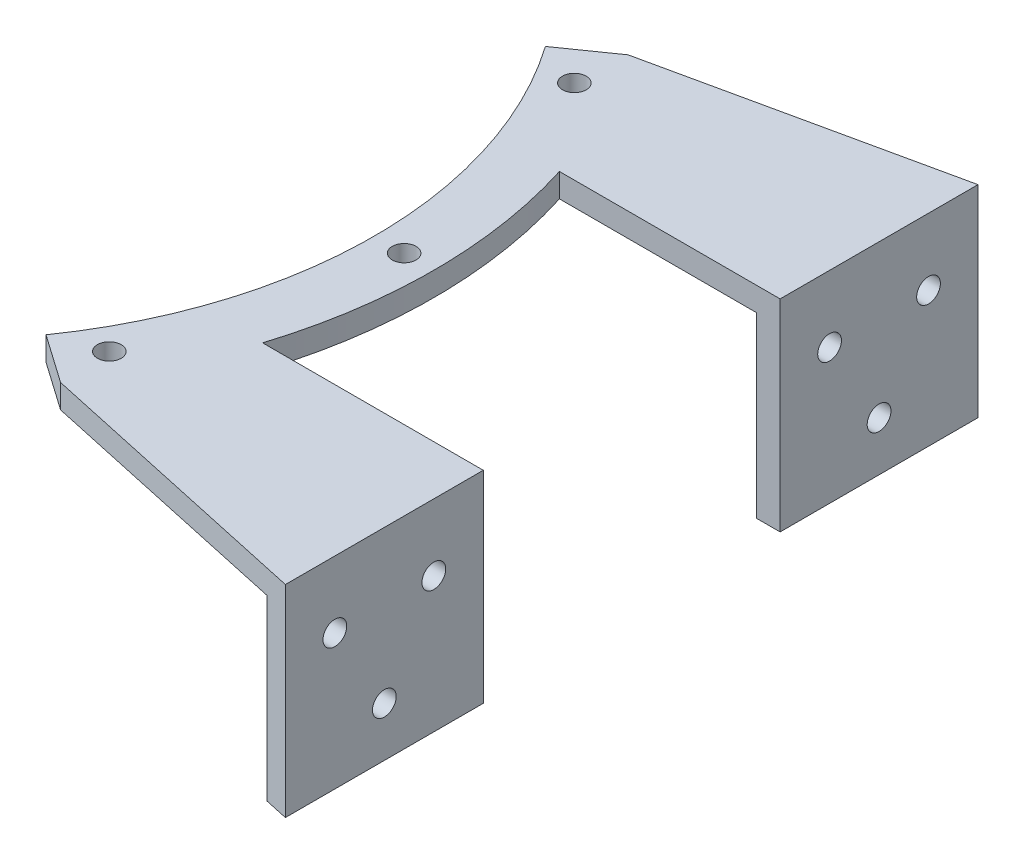
SolidWorks part; units mm, degrees
ref_plane "Front Plane" through (0, 0, 0) normal (0, 0, 1) x (1, 0, 0)
ref_plane "Top Plane" through (0, 0, 0) normal (0, 1, 0) x (1, 0, 0)
ref_plane "Right Plane" through (0, 0, 0) normal (1, 0, 0) x (0, 0, -1)
sketch "Sketch1" plane through (0, 0, 0) normal (0, 1, 0) x (1, 0, 0)
  line L0 (0, 0) -> (250, 0) construction
  line L1 (0, 0) -> (216.5064, 125) construction
  line L2 (0, 0) -> (216.5064, -125) construction
  line L3 (216.5064, 125) -> (216.5064, -125) construction
  line L5 (204.788, 143.3941) -> (204.788, -143.3941) construction
  line L11 (350, 175) -> (350, 75)
  line L12 (350, 75) -> (238.4848, 75)
  line L13 (350, -175) -> (350, -75)
  line L14 (350, -75) -> (238.4848, -75)
  line L15 (0, 0) -> (204.788, 143.3941) construction
  line L16 (0, 0) -> (204.788, -143.3941) construction
  line L17 (180.2134, 126.1868) -> (204.788, 143.3941)
  line L18 (180.2134, -126.1868) -> (204.788, -143.3941)
  line L21 (204.788, 143.3941) -> (350, 175)
  line L22 (204.788, -143.3941) -> (350, -175)
  arc A0 (180.2134, -126.1868) -> (180.2134, 126.1868) centre (0, 0) ccw
  arc A1 (204.788, -143.3941) -> (204.788, 143.3941) centre (0, 0) ccw construction
  circle A2 centre (0, 0) radius 235 construction
  circle A3 centre (203.516, -117.5) radius 6
  circle A4 centre (235, 0) radius 6
  circle A5 centre (203.516, 117.5) radius 6
  arc A8 (238.4848, -75) -> (238.4848, 75) centre (0, 0) ccw
  dimension "D11" = 250
  dimension "D2" = 220
  dimension "D4" = 470
  dimension "D5" = 12
  dimension "D3" = 60
  dimension "D6" = 100
  dimension "D7" = 100
  dimension "D8" = 350
  dimension "D9" = 70
  dimension "D10" = 350
extrude "Boss-Extrude2" add sketch "Sketch1" along normal blind 12
sketch "Sketch2" plane through (0, 0, 0) normal (0, -1, 0) x (-1, 0, 0)
  line L0 (-350, -175) -> (-350, -75)
  line L1 (-350, -75) -> (-338, -75)
  line L2 (-350, -75) -> (-238.4848, -75) construction
  line L3 (-338, -75) -> (-338, -172.3882)
  line L4 (-204.788, -143.3941) -> (-350, -175) construction
  line L5 (-338, -172.3882) -> (-350, -175)
  line L6 (-350, 75) -> (-350, 175)
  line L7 (-350, 175) -> (-338, 172.3882)
  line L8 (-350, 175) -> (-204.788, 143.3941) construction
  line L9 (-338, 172.3882) -> (-338, 75)
  line L10 (-238.4848, 75) -> (-350, 75) construction
  line L11 (-338, 75) -> (-350, 75)
  dimension "D1" = 12
extrude "Boss-Extrude3" add sketch "Sketch2" along normal blind 90
sketch "Sketch4" plane through (338, 0, 0) normal (-1, 0, 0) x (0, 0, 1)
  line L0 (-55.6551, -65) -> (-154.4826, -65) construction
  line L3 (0, 0) -> (0, -141.9458) construction
  circle A0 centre (-150, -21.6987) radius 6
  circle A6 centre (-125, -65) radius 6
  circle A7 centre (-100, -21.6987) radius 6
  circle A8 centre (125, -65) radius 6
  circle A9 centre (150, -21.6987) radius 6
  circle A10 centre (100, -21.6987) radius 6
  dimension "D5" = 12
  dimension "D1" = 65
  dimension "D2" = 50
  dimension "D3" = 50
  dimension "D4" = 50
  dimension "D6" = 150
extrude "Cut-Extrude1" cut sketch "Sketch4" against normal through all
equation "\"mbtOD\" = 600"
equation "\"mbtT\" = 6"
equation "\"mbtL\" = 3000"
equation "\"mbtFlangeOD\" = 700"
equation "\"mbtFlangeT\" = 12"
equation "\"mbtFlangeBoltCircleDia\" = 650"
equation "\"mbtFlangeHoleDia\" = 12"
equation "\"mbtOringSize\" = 10 "
equation "\"mbtOringDia\" = 620"
equation "\"mbtWidth\" = 2250"
equation "\"skiWidth\" = 1250"
equation "\"mbtCapL\" = 500"
equation "\"vbtRearOD\" = 500"
equation "\"vbtRearT\" = 6.25"
equation "\"vbtRearFlangeOD\" = 600"
equation "\"vbtRearFlangeT\" = 12"
equation "\"vbtRearBoltHoleDia\" = 12"
equation "\"vbtFrontOD\" = 440"
equation "\"vbtFrontT\" = 25"
equation "\"vbtFrontFlangeOD\" = 500"
equation "\"vbtFrontFlangeT\" = 12"
equation "\"vbtFrontBoltHoleDia\" = 12"
equation "\"D8@Sketch1\"=\"vbtFrontFlangeOD\"/2+100mm"
equation "\"D1@Boss-Extrude2\"=\"vbtRearFlangeT\""
equation "\"D11@Sketch1\"=\"vbtFrontFlangeOD\"/2"
equation "\"D2@Sketch1\"=\"vbtFrontOD\"/2"
equation "\"D4@Sketch1\"=(\"vbtFrontOD\"+\"vbtFrontFlangeOD\")/2"
equation "\"D5@Sketch1\"=\"vbtFrontBoltHoleDia\""
equation "\"D1@Sketch2\"=\"vbtFrontFlangeT\""
